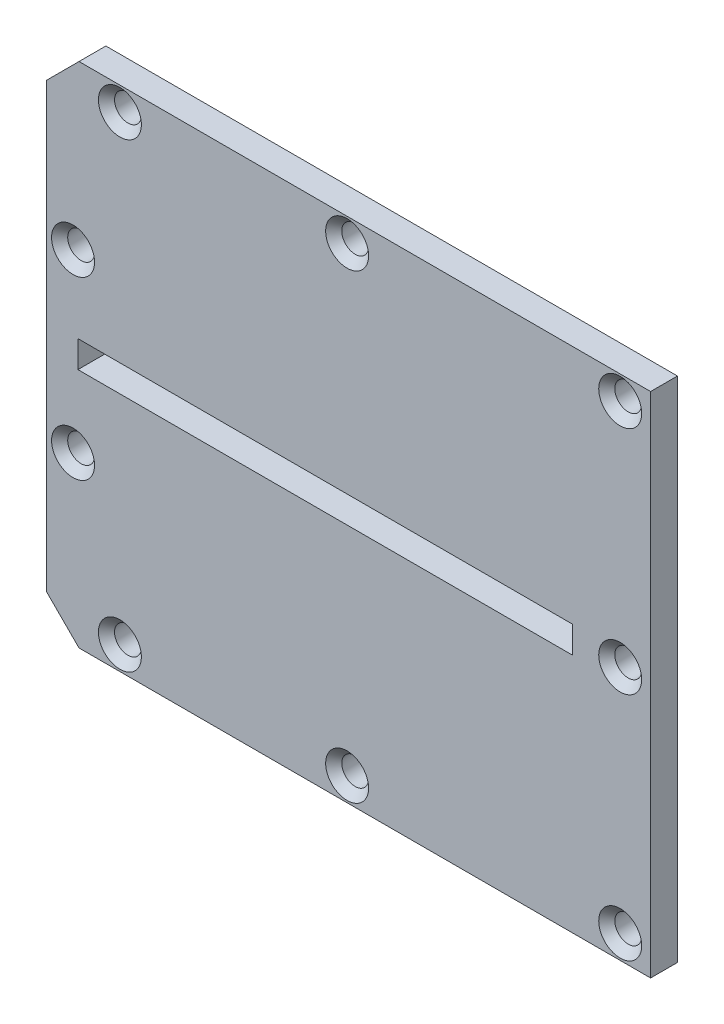
SolidWorks part; units mm, degrees
ref_plane "Front Plane" through (0, 0, 0) normal (0, 0, 1) x (1, 0, 0)
ref_plane "Top Plane" through (0, 0, 0) normal (0, 1, 0) x (1, 0, 0)
ref_plane "Right Plane" through (0, 0, 0) normal (1, 0, 0) x (0, 0, -1)
sketch "Sketch1" plane through (0, 0, 0) normal (0, 0, 1) x (1, 0, 0)
  line L1 (-102.9313, 19.5835) -> (-56.0944, 19.5835) construction
  line L2 (-102.9313, 19.5835) -> (-102.9313, -19.5835) construction
  line L3 (-102.9313, -19.5835) -> (-56.0944, -19.5835) construction
  line L4 (-56.0944, 19.5835) -> (-56.0944, -19.5835) construction
  line L6 (-104.8778, -24.0272) -> (-50.8, -24.0272)
  line L7 (-50.8, -24.0272) -> (-50.8, 24.0272)
  line L8 (-50.8, 24.0272) -> (-104.8778, 24.0272)
  line L9 (-104.8778, 24.0272) -> (-107.95, 20.955)
  line L10 (-107.95, 20.955) -> (-107.95, -20.955)
  line L11 (-107.95, -20.955) -> (-104.8778, -24.0272)
  line L12 (-104.8778, -24.0272) -> (-50.8, -24.0272)
  line L13 (-50.8, -24.0272) -> (-50.8, 24.0272)
  line L14 (-50.8, 24.0272) -> (-104.8778, 24.0272)
  line L15 (-104.8778, 24.0272) -> (-107.95, 20.955)
  line L16 (-107.95, 20.955) -> (-107.95, -20.955)
  line L17 (-107.95, -20.955) -> (-104.8778, -24.0272)
  circle A0 centre (-101.0095, 21.8054) radius 1.27
  circle A1 centre (-79.5128, 21.8054) radius 1.27
  circle A2 centre (-53.6769, 21.8054) radius 1.27
  circle A3 centre (-53.6769, 0) radius 1.27
  circle A4 centre (-53.6769, -21.8054) radius 1.27
  circle A5 centre (-79.5128, -21.8054) radius 1.27
  circle A6 centre (-101.0095, -21.8054) radius 1.27
  circle A7 centre (-105.4406, -8.3201) radius 1.27
  circle A8 centre (-105.4406, 8.3201) radius 1.27
  dimension "D1" = 0
extrude "Boss-Extrude1" add sketch "Sketch1" along normal blind 2.54
chamfer "Chamfer1" distance 0.762 angle 45 9 edges at (-104.1706, 8.3201, 2.54) (-104.1706, -8.3201, 2.54) (-99.7395, -21.8054, 2.54) (-78.2428, -21.8054, 2.54) (-52.4069, -21.8054, 2.54) (-52.4069, 0, 2.54) (-52.4069, 21.8054, 2.54) (-78.2428, 21.8054, 2.54) (-99.7395, 21.8054, 2.54)
sketch "Sketch2" plane through (0, 0, 2.54) normal (0, 0, 1) x (1, 0, 0)
  line L0 (-107.95, 0) -> (-50.8, 0) construction
  line L1 (-104.983, 1.27) -> (-58.1832, 1.27)
  line L2 (-104.983, 1.27) -> (-104.983, -1.27)
  line L3 (-104.983, -1.27) -> (-58.1832, -1.27)
  line L4 (-58.1832, 1.27) -> (-58.1832, -1.27)
  line L5 (-107.95, 20.955) -> (-107.95, -20.955) construction
  line L6 (-50.8, -24.0272) -> (-50.8, 24.0272) construction
  point P10 (-104.983, 0)
  dimension "D1" = 2.54
extrude "Cut-Extrude1" cut sketch "Sketch2" against normal blind 5.334
